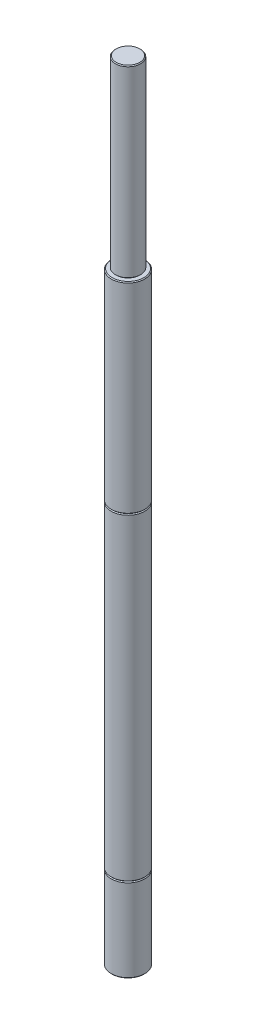
SolidWorks part; units mm, degrees
ref_plane "Front Plane" through (0, 0, 0) normal (0, 0, 1) x (1, 0, 0)
ref_plane "Top Plane" through (0, 0, 0) normal (0, 1, 0) x (1, 0, 0)
ref_plane "Right Plane" through (0, 0, 0) normal (1, 0, 0) x (0, 0, -1)
sketch "Sketch1" plane through (0, 0, 0) normal (0, 1, 0) x (1, 0, 0)
  circle A0 centre (0, 0) radius 1.5
  dimension "D1" = 3
extrude "Boss-Extrude1" add sketch "Sketch1" along normal blind 22
sketch "Sketch2" plane through (0, 0, 0) normal (0, -1, 0) x (1, 0, 0)
  circle A0 centre (0, 0) radius 2
  dimension "D1" = 4
extrude "Boss-Extrude2" add sketch "Sketch2" along normal blind 24 separate body
sketch "Sketch3" plane through (0, -24, 0) normal (0, -1, 0) x (1, 0, 0)
  circle A1 centre (0, 0) radius 2
  circle A2 centre (0, 0) radius 2
  dimension "D1" = 0
extrude "Boss-Extrude3" add sketch "Sketch3" along normal blind 38 separate body
sketch "Sketch4" plane through (0, -62, 0) normal (0, -1, 0) x (1, 0, 0)
  circle A1 centre (0, 0) radius 2
  circle A2 centre (0, 0) radius 2
  dimension "D1" = 0
extrude "Boss-Extrude4" add sketch "Sketch4" along normal blind 10 separate body
chamfer "Chamfer1" distance 0.1 angle 45 2 edges at (0, -62, -2) (0, -72, -2)
chamfer "Chamfer2" distance 0.1 angle 45 2 edges at (0, -24, -2) (0, -62, -2)
chamfer "Chamfer3" distance 0.1 angle 45 2 edges at (0, 0, -2) (0, -24, -2)
chamfer "Chamfer4" distance 0.1 angle 45 2 edges at (0, 0, 1.5) (0, 22, 1.5)
